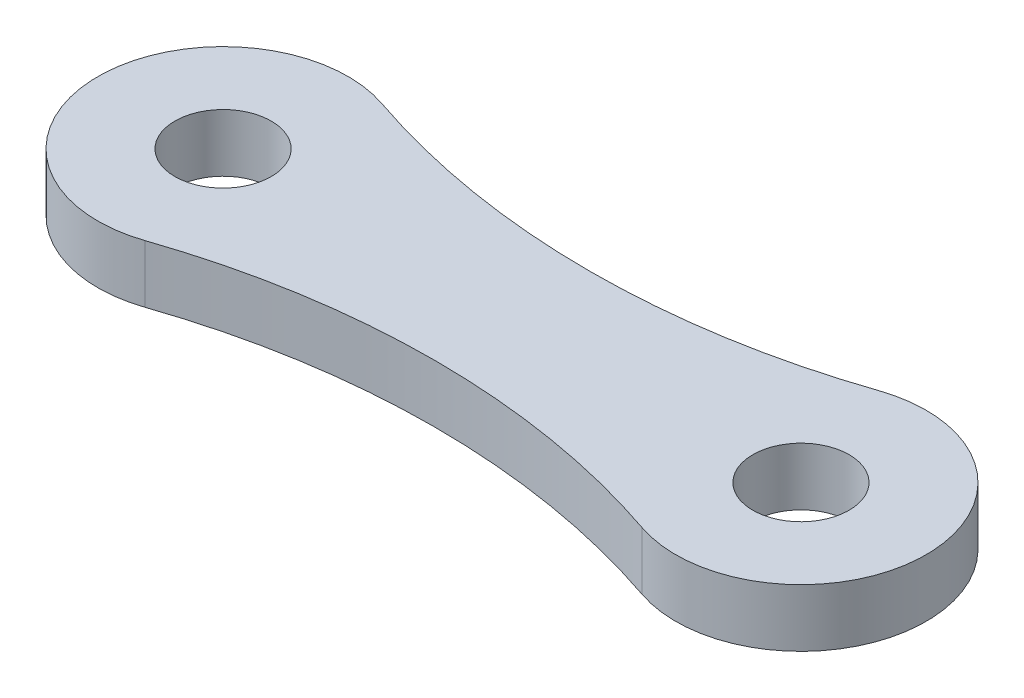
SolidWorks part; units mm, degrees
material "碳板"
ref_plane "前视基准面" through (0, 0, 0) normal (0, 0, 1) x (1, 0, 0)
ref_plane "上视基准面" through (0, 0, 0) normal (0, 1, 0) x (1, 0, 0)
ref_plane "右视基准面" through (0, 0, 0) normal (1, 0, 0) x (0, 0, -1)
sketch "草图1" plane through (0, 0, 0) normal (0, 1, 0) x (1, 0, 0)
  line L0 (0, 38.7725) -> (0, -41.1683) construction
  line L1 (-47.5358, 0) -> (43.5009, 0) construction
  circle A0 centre (-15, 0) radius 2.5
  arc A1 (-12.9032, 6.1525) -> (-12.9032, -6.1525) centre (-15, 0) ccw
  circle A2 centre (15, 0) radius 2.5
  arc A3 (12.9032, 6.1525) -> (12.9032, -6.1525) centre (15, 0) cw
  arc A4 (-12.9032, 6.1525) -> (12.9032, 6.1525) centre (0, 44.0142) ccw
  arc A5 (-12.9032, -6.1525) -> (12.9032, -6.1525) centre (0, -44.0142) cw
  circle A7 centre (-15, 0) radius 6.5 construction
  point P19 (-8.784, 1.9004)
  dimension "D1" = 5
  dimension "D4" = 40
  dimension "D3" = 30
  dimension "D2" = 4
extrude "凸台-拉伸1" add sketch "草图1" along normal blind 3
move or copy body "实体-移动/复制1" [suppressed] bodies to move or copy 106
